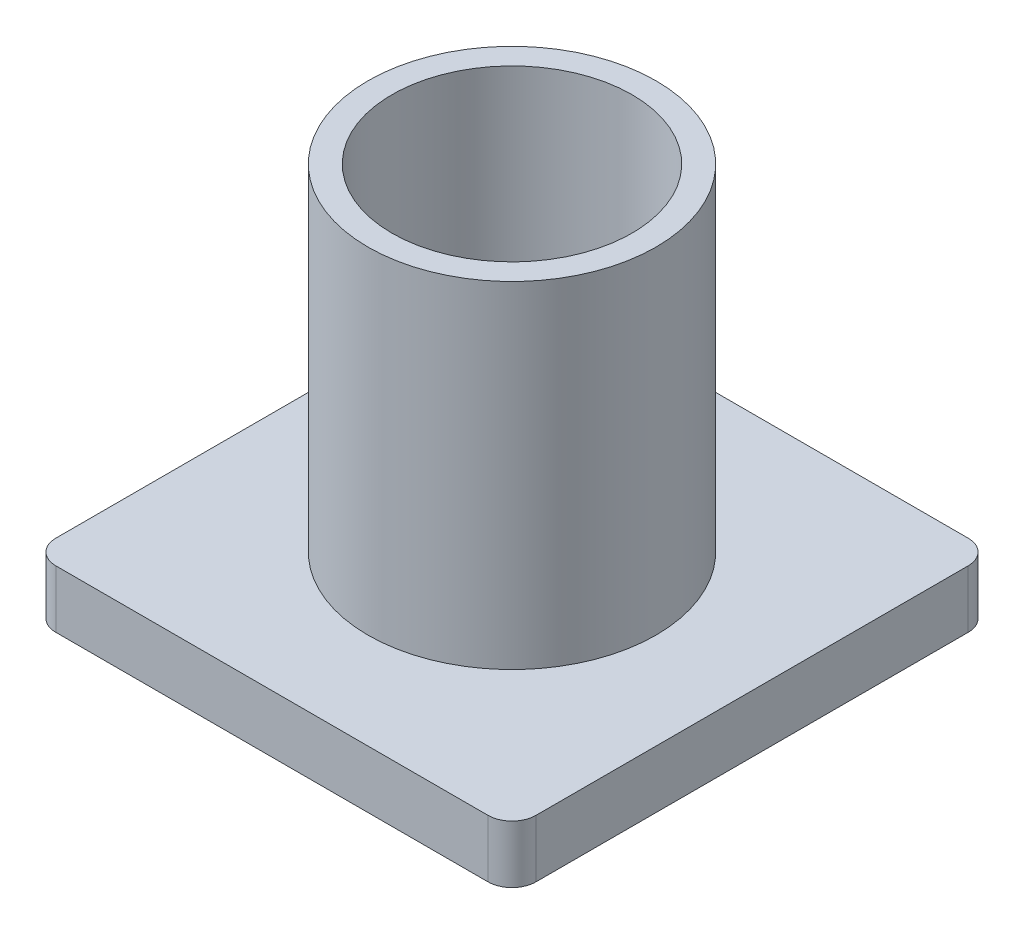
SolidWorks part; units mm, degrees
ref_plane "Front Plane" through (0, 0, 0) normal (0, 0, 1) x (1, 0, 0)
ref_plane "Top Plane" through (0, 0, 0) normal (0, 1, 0) x (1, 0, 0)
ref_plane "Right Plane" through (0, 0, 0) normal (1, 0, 0) x (0, 0, -1)
sketch "Sketch1" plane through (0, 0, 0) normal (0, 1, 0) x (1, 0, 0)
  line L0 (-50, 50) -> (50, -50) construction
  line L1 (-45, 50) -> (45, 50)
  line L2 (-50, 45) -> (-50, -45)
  line L3 (-45, -50) -> (45, -50)
  line L4 (50, 45) -> (50, -45)
  line L5 (-50, -50) -> (50, 50) construction
  arc A0 (-45, 50) -> (-50, 45) centre (-45, 45) ccw
  arc A1 (45, 50) -> (50, 45) centre (45, 45) cw
  arc A2 (45, -50) -> (50, -45) centre (45, -45) ccw
  arc A3 (-50, -45) -> (-45, -50) centre (-45, -45) ccw
  point P0 (0, 0)
  dimension "D1" = 5
  dimension "D2" = 100
  dimension "D3" = 100
extrude "Boss-Extrude1" add sketch "Sketch1" along normal blind 12
sketch "Sketch3" plane through (0, 12, 0) normal (0, 1, 0) x (1, 0, 0)
  circle A0 centre (0, 0) radius 30
  dimension "D1" = 60
extrude "Boss-Extrude2" add sketch "Sketch3" along normal blind 70
sketch "Sketch4" plane through (0, 82, 0) normal (0, 1, 0) x (1, 0, 0)
  circle A0 centre (0, 0) radius 25
  dimension "D1" = 50
extrude "Cut-Extrude1" cut sketch "Sketch4" against normal blind 70
